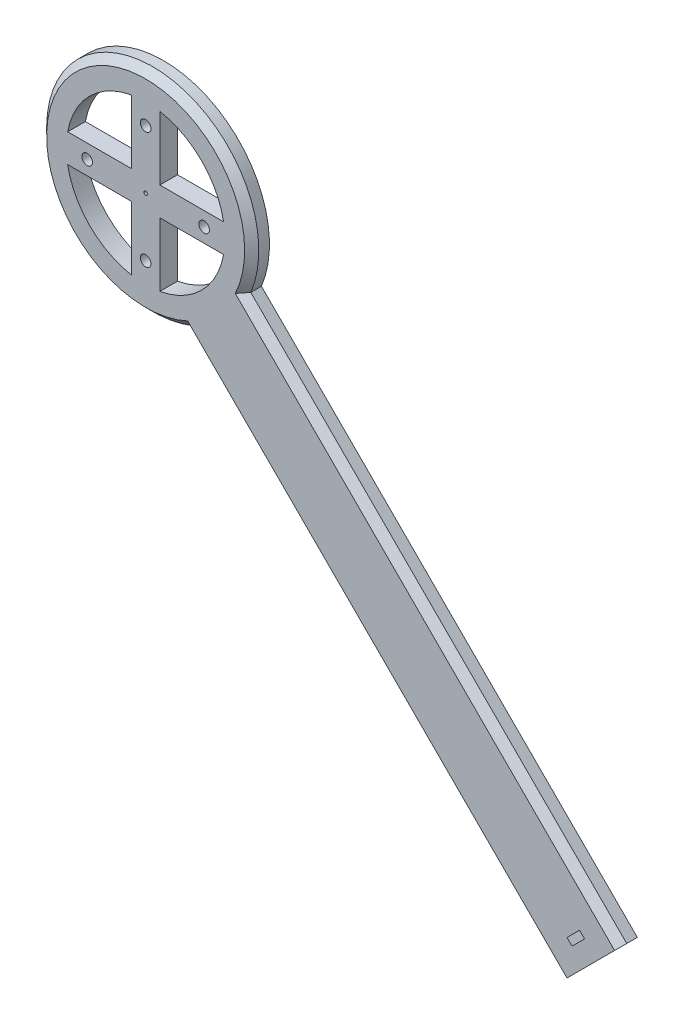
SolidWorks part; units mm, degrees
ref_plane "Plan de face" through (0, 0, 0) normal (0, 0, 1) x (1, 0, 0)
ref_plane "Plan de dessus" through (0, 0, 0) normal (0, 1, 0) x (1, 0, 0)
ref_plane "Plan de droite" through (0, 0, 0) normal (1, 0, 0) x (0, 0, -1)
sketch "Esquisse3" plane through (0, 0, 0) normal (0, 0, 1) x (1, 0, 0)
  line L0 (-16.5, -1.4697) -> (16.5, -1.4697) construction
  line L1 (16.5, -1.4697) -> (0, 15.0303) construction
  line L2 (0, -17.9697) -> (0, 15.0303) construction
  line L5 (0, 15.0303) -> (-16.5, -1.4697) construction
  line L6 (-16.5, -1.4697) -> (0, -17.9697) construction
  line L7 (0, -17.9697) -> (16.5, -1.4697) construction
  circle A4 centre (0, 15.0303) radius 1.5
  circle A5 centre (16.5, -1.4697) radius 1.5
  circle A6 centre (0, -17.9697) radius 1.5
  circle A7 centre (-16.5, -1.4697) radius 1.5
  circle A8 centre (0, -1.4697) radius 0.5
  point P19 (0, -1.4697)
  dimension "D2" = 4
  dimension "D3" = 3
  dimension "D1" = 33
sketch "Esquisse6" plane through (0, 0, 0) normal (0, 0, 1) x (1, 0, 0)
  line L0 (-14.3337, -1.4697) -> (14.3337, -1.4697) construction
  line L1 (14.3337, -1.4697) -> (0, -1.4697) construction
  line L2 (0, -1.4697) -> (0, -15.8033) construction
  line L3 (0, -15.8033) -> (0, 12.864) construction
  line L4 (-4, -23.4697) -> (-4, -5.4697)
  line L5 (-4, -5.4697) -> (-22, -5.4697)
  line L6 (-4, 2.5303) -> (-4, 20.5303)
  line L7 (-22, 2.5303) -> (-4, 2.5303)
  line L8 (4, 2.5303) -> (22, 2.5303)
  line L9 (4, 20.5303) -> (4, 2.5303)
  line L10 (4, -5.4697) -> (4, -23.4697)
  line L11 (22, -5.4697) -> (4, -5.4697)
  line L12 (0, -1.4697) -> (31.7407, -33.2103) construction
  line L13 (11.4099, -29.143) -> (27.6734, -12.8796) construction
  line L14 (11.4099, -29.143) -> (117.4759, -135.209)
  line L15 (117.4759, -135.209) -> (133.7394, -118.9456)
  line L16 (133.7394, -118.9456) -> (27.6734, -12.8796)
  arc A2 (-22, 2.5303) -> (-4, 20.5303) centre (0, -1.4697) cw
  arc A3 (4, 20.5303) -> (22, 2.5303) centre (0, -1.4697) cw
  arc A4 (22, -5.4697) -> (4, -23.4697) centre (0, -1.4697) cw
  arc A5 (-4, -23.4697) -> (-22, -5.4697) centre (0, -1.4697) cw
  arc A6 (11.4099, -29.143) -> (27.6734, -12.8796) centre (0, -1.4697) cw
  point P13 (19.5416, -21.0113)
  dimension "D1" = 4
  dimension "D4" = 18
  dimension "D5" = 150
  dimension "D2" = 4
  dimension "D6" = 18
  dimension "D7" = 23
  dimension "D3" = 4
extrude "Boss.-Extru.1" add sketch "Esquisse6" along normal blind 5
extrude "Enlèv. mat.-Extru.1" cut sketch "Esquisse3" along normal blind 5
sketch "Esquisse7" plane through (126.3425, -126.3425, 0) normal (0.7071, -0.7071, 0) x (0, 0, -1)
  line L0 (0, -12.5392) -> (-5, 10.4608) construction
  line L1 (-5, 10.4608) -> (0, 10.4608) construction
  line L2 (0, 10.4608) -> (-5, -12.5392) construction
  line L3 (-2.5, -1.0392) -> (5, -1.0392) construction
  line L4 (5, -1.0392) -> (0, -1.0392) construction
  line L5 (0, -12.5392) -> (0, 10.4608) construction
  line L7 (-5, 10.4608) -> (0, 10.4608)
  line L8 (5, -3.5392) -> (0, -3.5392)
  line L9 (5, -3.5392) -> (5, 1.4608)
  line L10 (5, 1.4608) -> (0, 1.4608)
  line L12 (5, -3.5392) -> (0, 1.4608) construction
  line L13 (5, 1.4608) -> (0, -3.5392) construction
  line L14 (0, 10.4608) -> (0, 1.4608)
  line L15 (5, 1.4608) -> (5, -3.5392)
  line L16 (0, -3.5392) -> (0, -12.5392)
  line L17 (0, -12.5392) -> (-5, -12.5392)
  line L18 (-5, -12.5392) -> (-5, 10.4608)
  point P10 (2.5, -1.0392)
  line M5 (0, -12.5392) -> (0, 10.4608)
  line M6 (0, 10.4608) -> (-5, 10.4608)
  line M7 (-5, 10.4608) -> (-5, -12.5392)
  line M8 (-5, -12.5392) -> (0, -12.5392)
  dimension "D1" = 5
  dimension "D2" = 5
  dimension "D3" = 5
extrude "Boss.-Extru.2" add sketch "Esquisse7" against normal blind 146 contours M8 M5 M6 M7 | L9 L10 L8 M5
chamfer "Chanfrein1" distance 2 angle 45 3 edges at (80.7064, -65.9126, 5) (-21.166, 19.6964, 5) (64.4429, -82.176, 5)
sketch "Esquisse8" plane through (0, 0, 5) normal (0, 0, 1) x (1, 0, 0)
  line L1 (120.3043, -125.3095) -> (123.8399, -121.774)
  line L2 (120.3043, -125.3095) -> (118.8901, -123.8953)
  line L3 (118.8901, -123.8953) -> (122.4257, -120.3598)
  line L4 (123.8399, -121.774) -> (122.4257, -120.3598)
  line L5 (121.365, -122.8347) -> (125.6076, -127.0773) construction
  line L6 (118.8901, -133.7948) -> (132.3252, -120.3598) construction
  line L7 (120.3043, -125.3095) -> (122.4257, -120.3598) construction
  line L8 (118.8901, -123.8953) -> (123.8399, -121.774) construction
  dimension "D1" = 6
extrude "Enlèv. mat.-Extru.2" cut sketch "Esquisse8" against normal blind 146
